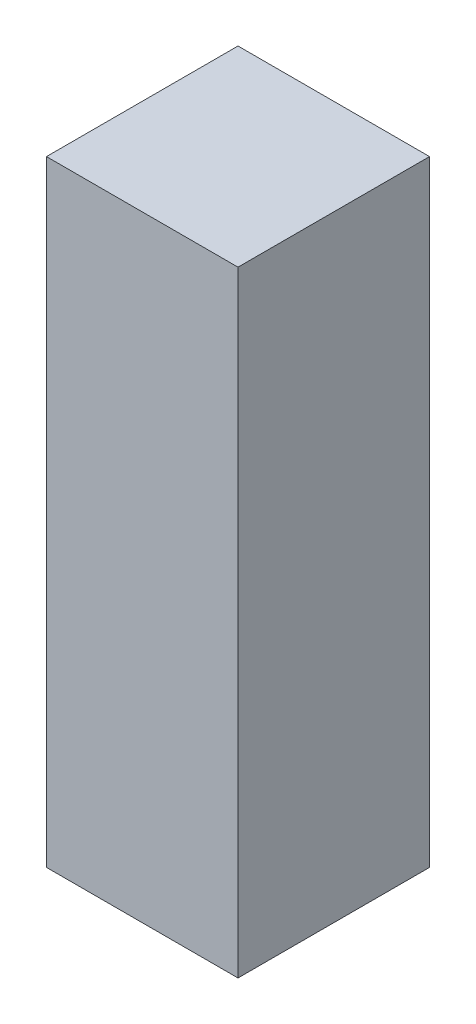
SolidWorks part; units mm, degrees
ref_plane "Front Plane" through (0, 0, 0) normal (0, 0, 1) x (1, 0, 0)
ref_plane "Top Plane" through (0, 0, 0) normal (0, 1, 0) x (1, 0, 0)
ref_plane "Right Plane" through (0, 0, 0) normal (1, 0, 0) x (0, 0, -1)
sketch "Sketch1" plane through (0, 0, 0) normal (0, 1, 0) x (1, 0, 0)
  line L1 (35, -35) -> (-35, -35)
  line L2 (35, -35) -> (35, 35)
  line L3 (35, 35) -> (-35, 35)
  line L4 (-35, -35) -> (-35, 35)
  line L5 (35, -35) -> (-35, 35) construction
  line L6 (35, 35) -> (-35, -35) construction
  point P0 (0, 0)
  dimension "D1" = 70
  dimension "D2" = 70
extrude "Boss-Extrude1" add sketch "Sketch1" along normal blind 225
